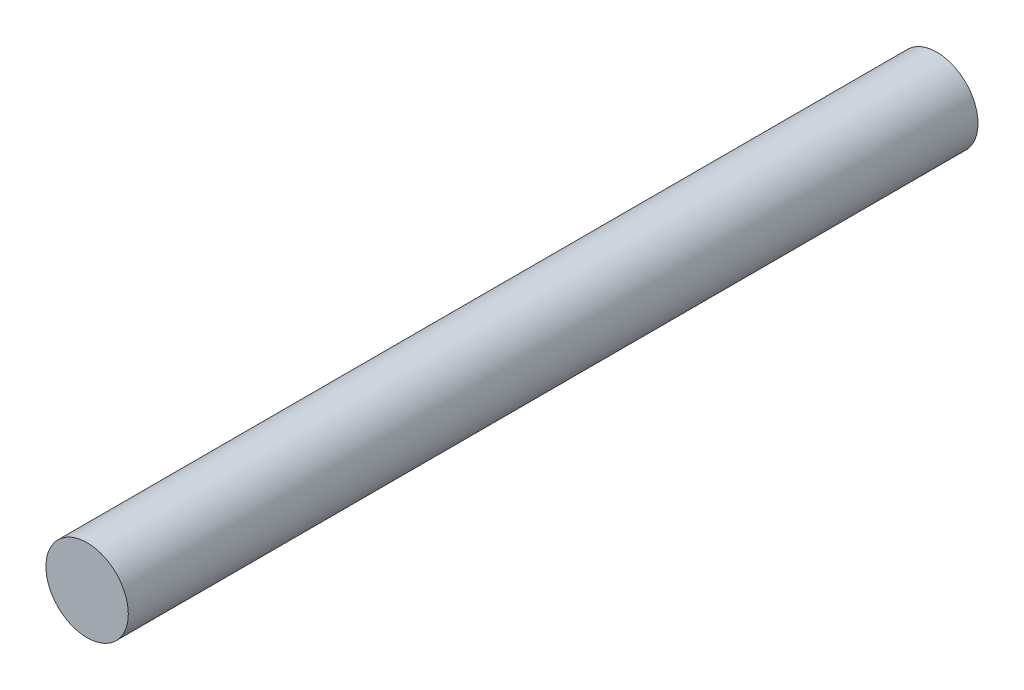
SolidWorks part; units mm, degrees
ref_plane "Front Plane" through (0, 0, 0) normal (0, 0, 1) x (1, 0, 0)
ref_plane "Top Plane" through (0, 0, 0) normal (0, 1, 0) x (1, 0, 0)
ref_plane "Right Plane" through (0, 0, 0) normal (1, 0, 0) x (0, 0, -1)
sketch "Sketch1" plane through (0, 0, 0) normal (0, 0, 1) x (1, 0, 0)
  circle A0 centre (0, 0) radius 4.064
  dimension "D1" = 8.128
extrude "Boss-Extrude1" add sketch "Sketch1" along normal blind 83.82
